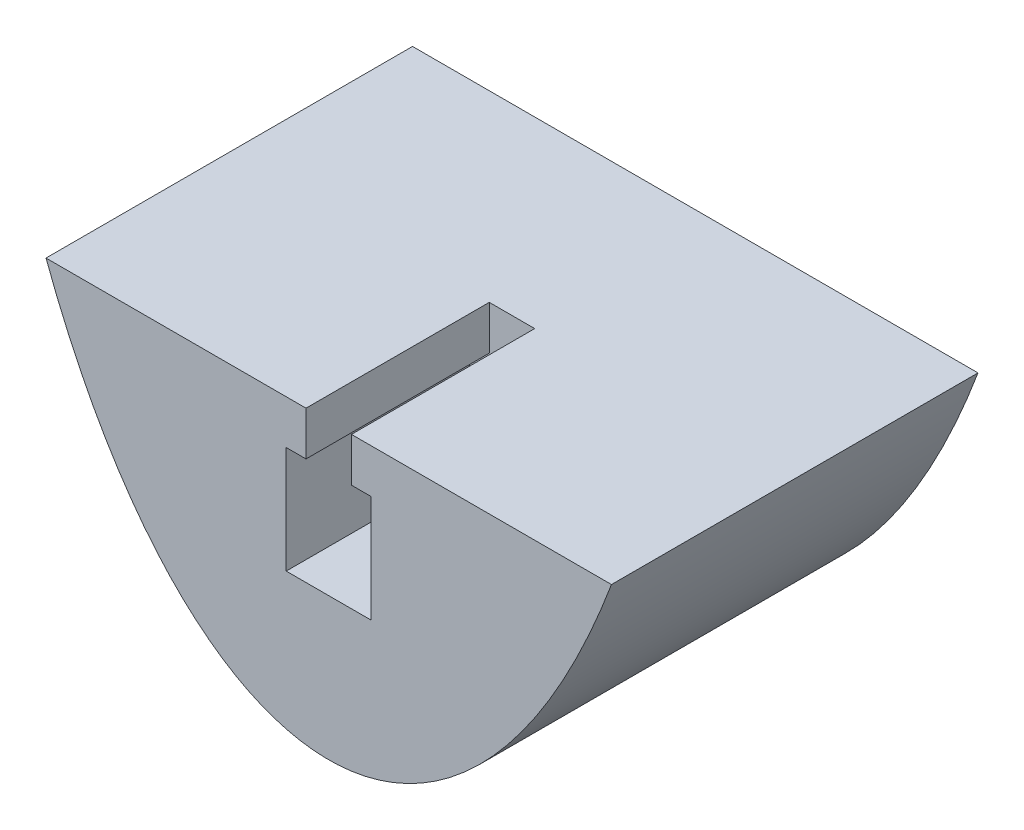
SolidWorks part; units mm, degrees
ref_plane "Alzado" through (0, 0, 0) normal (0, 0, 1) x (1, 0, 0)
ref_plane "Planta" through (0, 0, 0) normal (0, 1, 0) x (1, 0, 0)
ref_plane "Vista lateral" through (0, 0, 0) normal (1, 0, 0) x (0, 0, -1)
sketch "Croquis9" plane through (0, 0, 0) normal (0, 0, 1) x (1, 0, 0)
  line L0 (5.4384, -64.9459) -> (44.0079, -64.9459)
  ellipse E0 centre (24.7232, -29.9459) end of major axis (24.7232, -84.9459) minor radius 25 (5.4384, -64.9459) -> (44.0079, -64.9459) ccw
extrude "Saliente-Extruir6" add sketch "Croquis9" along normal blind 25 separate body
sketch "Croquis10" plane through (0, -64.9459, 0) normal (0, 1, 0) x (1, 0, 0)
  line L7 (44.0079, -25) -> (5.4384, -25) construction
  line L9 (23.1729, -12.5) -> (26.2729, -12.5)
  line L10 (23.1729, -12.5) -> (23.1729, -25)
  line L11 (26.2729, -12.5) -> (26.2729, -25)
  line L12 (23.1729, -25) -> (26.2729, -25)
  line L13 (44.0079, -25) -> (44.0079, 0) construction
  dimension "D1" = 3.1
  dimension "D2" = 17.735
  dimension "D3" = 12.5
  dimension "D4" = 0
extrude "Cortar-Extruir1" cut sketch "Croquis10" against normal blind 3
sketch "Croquis14" plane through (0, -67.9459, 0) normal (0, 1, 0) x (1, 0, 0)
  line L0 (21.8229, -25) -> (21.8229, -12.5)
  line L1 (21.8229, -25) -> (27.6229, -25)
  line L2 (21.8229, -12.5) -> (27.6229, -12.5)
  line L3 (27.6229, -25) -> (27.6229, -12.5)
  line L4 (23.1729, -25) -> (26.2729, -25) construction
  line L5 (23.1729, -12.5) -> (26.2729, -12.5) construction
  line L8 (44.0079, -25) -> (44.0079, 0) construction
  dimension "D1" = 5.8
  dimension "D2" = 16.385
extrude "Cortar-Extruir3" cut sketch "Croquis14" against normal blind 7.3
